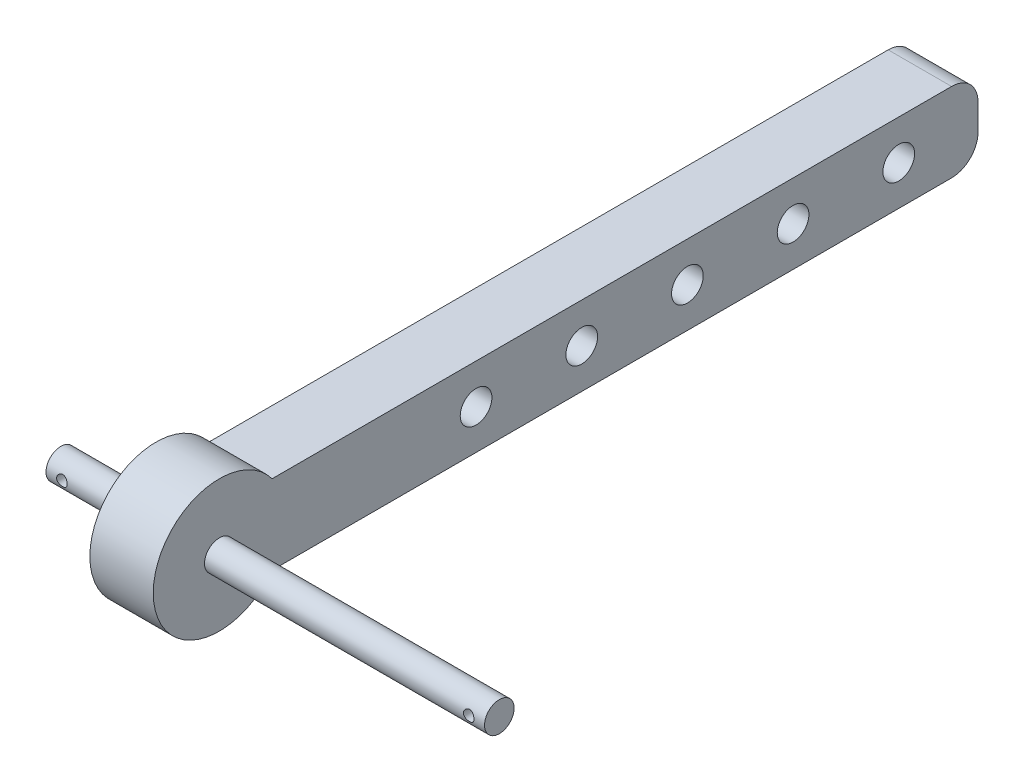
SolidWorks part; units mm, degrees
ref_plane "前视基准面" through (0, 0, 0) normal (0, 0, 1) x (1, 0, 0)
ref_plane "上视基准面" through (0, 0, 0) normal (0, 1, 0) x (1, 0, 0)
ref_plane "右视基准面" through (0, 0, 0) normal (1, 0, 0) x (0, 0, -1)
other "Configuration Table"
sketch "草图1" plane through (0, 0, 0) normal (1, 0, 0) x (0, 0, -1)
  line L1 (0, 0) -> (150, 0)
  line L2 (0, 0) -> (0, 15)
  line L3 (0, 15) -> (150, 15)
  line L4 (150, 0) -> (150, 15)
  dimension "D1" = 15
  dimension "D2" = 150
extrude "凸台-拉伸1" add sketch "草图1" along normal blind 12
fillet "圆角1" radius 5 4 edges at (6, 0, -150) (6, 15, -150) (6, 0, 0) (6, 15, 0)
sketch "草图6" plane through (12, 0, 0) normal (1, 0, 0) x (0, 0, -1)
  circle A0 centre (6.4, 7.5) radius 12.5
extrude "凸台-拉伸2" add sketch "草图6" against normal up to surface (12 mm away) up to face at (0, 7.5, -75)
sketch "草图15" plane through (0, 0, 0) normal (-1, 0, 0) x (0, 0, 1)
  circle A2 centre (-6.4, 7.5) radius 2.8
  dimension "D1" = 5.6
extrude "凸台-拉伸5" add sketch "草图15" along normal blind 18 and the other way blind 65
sketch "草图16" plane through (0, 0, 0) normal (0, 0, 1) x (1, 0, 0)
  line L0 (-18, 7.5) -> (-24.7951, 7.5) construction
  line L1 (-18, 10.3) -> (-18, 4.7) construction
  line L2 (65, 7.5) -> (28.4852, 7.5) construction
  line L3 (65, 4.7) -> (65, 10.3) construction
  circle A0 centre (-15, 7.5) radius 1
  circle A1 centre (62, 7.5) radius 1
  dimension "D2" = 2
  dimension "D3" = 2
  dimension "D1" = 3
  dimension "D4" = 3
extrude "切除-拉伸9" cut sketch "草图16" against normal up to next
sketch "草图17" plane through (0, 0, 0) normal (-1, 0, 0) x (0, 0, 1)
  line L0 (-150, 7.5) -> (-31.7081, 7.5) construction
  line L1 (-150, 5) -> (-150, 10) construction
  circle A0 centre (-135, 7.5) radius 3
  circle A1 centre (-115, 7.5) radius 3
  circle A2 centre (-95, 7.5) radius 3
  circle A3 centre (-75, 7.5) radius 3
  circle A4 centre (-55, 7.5) radius 3
  dimension "D6" = 6
  dimension "D7" = 6
  dimension "D8" = 6
  dimension "D9" = 6
  dimension "D10" = 6
  dimension "D1" = 15
  dimension "D2" = 20
  dimension "D3" = 20
  dimension "D4" = 20
  dimension "D5" = 20
extrude "切除-拉伸10" cut sketch "草图17" against normal up to next
